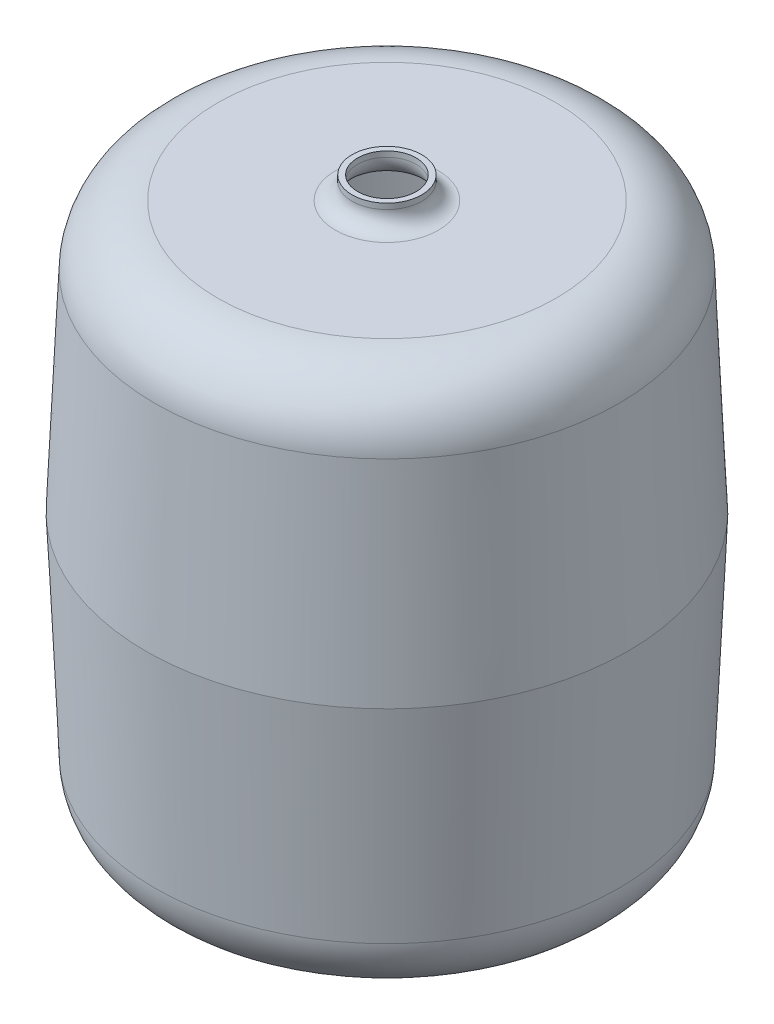
SolidWorks part; units mm, degrees
material "1060 Alloy"
ref_plane "Front Plane" through (0, 0, 0) normal (0, 0, 1) x (1, 0, 0)
ref_plane "Top Plane" through (0, 0, 0) normal (0, 1, 0) x (1, 0, 0)
ref_plane "Right Plane" through (0, 0, 0) normal (1, 0, 0) x (0, 0, -1)
sketch "Sketch1" plane through (0, 0, 0) normal (0, 0, 1) x (1, 0, 0)
  line L0 (-212.3884, 0) -> (206.7356, 0) construction
  line L1 (0, -193.75) -> (0, 209.75) construction
  line L2 (0, -193.75) -> (121.539, -193.75)
  line L3 (166.4962, -150.7129) -> (173.0765, 0)
  line L4 (173.0765, 0) -> (166.4962, 150.7129)
  line L5 (121.539, 193.75) -> (37, 193.75)
  line L7 (25, 209.75) -> (25, 205.75)
  line L17 (21, 209.75) -> (21, 205.75)
  line L18 (121.539, 189.75) -> (37, 189.75)
  line L19 (169.0726, 0) -> (162.5, 150.5384)
  line L20 (0, 209.75) -> (25, 209.75) construction
  line L21 (162.5, 150.5384) -> (162.5, 193.75) construction
  line L22 (162.5, 193.75) -> (121.539, 193.75) construction
  line L23 (166.4962, -150.7129) -> (166.4962, -193.75) construction
  line L24 (166.4962, -193.75) -> (121.539, -193.75) construction
  line L25 (162.5, -150.5384) -> (169.0726, 0)
  line L26 (0, -189.75) -> (121.539, -189.75)
  line L27 (21, 209.75) -> (25, 209.75)
  line L28 (0, -189.75) -> (0, -193.75)
  arc A0 (37, 193.75) -> (25, 205.75) centre (37, 205.75) cw
  arc A1 (121.539, -193.75) -> (166.4962, -150.7129) centre (121.539, -148.75) ccw
  arc A2 (166.4962, 150.7129) -> (121.539, 193.75) centre (121.539, 148.75) ccw
  arc A6 (37, 189.75) -> (21, 205.75) centre (37, 205.75) cw
  arc A7 (162.5, 150.5384) -> (121.539, 189.75) centre (121.539, 148.75) ccw
  arc A8 (121.539, -189.75) -> (162.5, -150.5384) centre (121.539, -148.75) ccw
  point P11 (25, 193.75)
  dimension "D7" = 12
  dimension "D8" = 45
  dimension "D2" = 387.5
  dimension "D3" = 92.5
  dimension "D4" = 92.5
  dimension "D5" = 50
  dimension "D9" = 20
  dimension "D1" = 325
  dimension "D6" = 4
revolve "Revolve4" add sketch "Sketch1" angle 360 about L1
equation "\"A\"= 325mm"
equation "\"B\"= 387.5mm"
equation "\"D2@Sketch1\"=\"B\""
